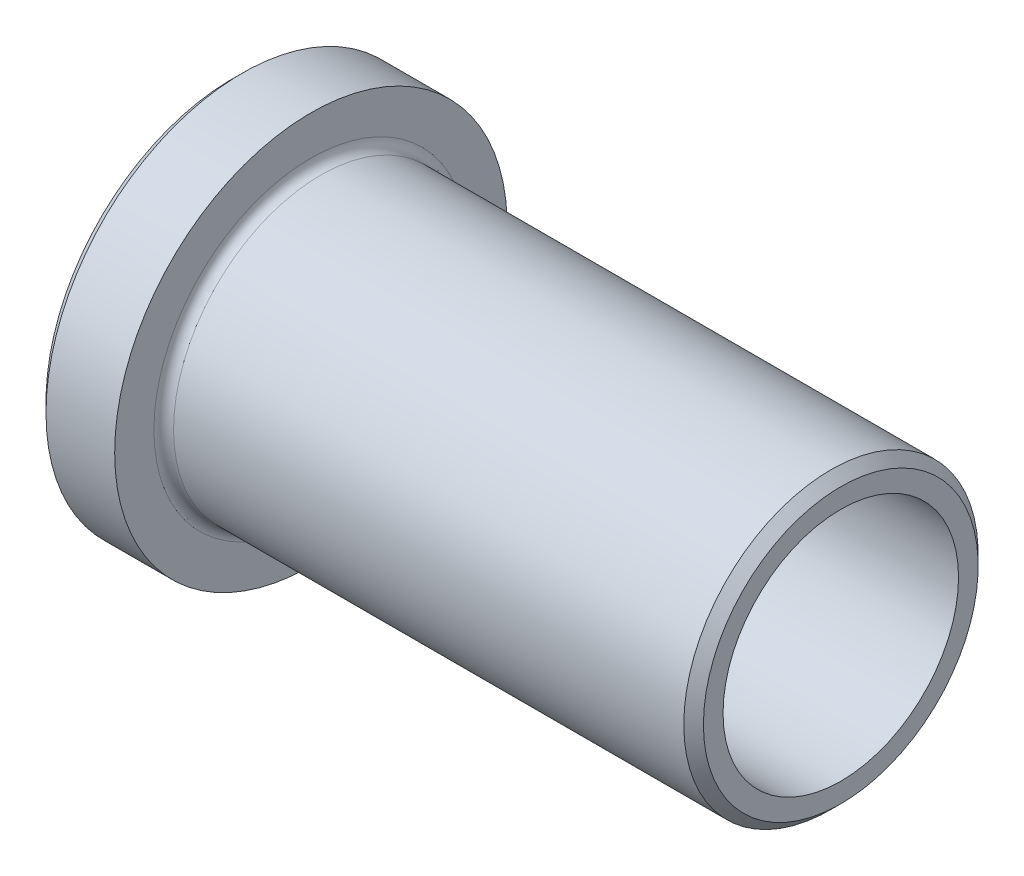
SolidWorks part; units mm, degrees
ref_plane "Piano frontale" through (0, 0, 0) normal (0, 0, 1) x (1, 0, 0)
ref_plane "Piano superiore" through (0, 0, 0) normal (0, 1, 0) x (1, 0, 0)
ref_plane "Piano destro" through (0, 0, 0) normal (1, 0, 0) x (0, 0, -1)
sketch "Sketch1" plane through (0, 0, 0) normal (0, 0, 1) x (1, 0, 0)
  line L0 (-6.1144, 0) -> (31, 0) construction
  line L1 (0, 6) -> (0, 10)
  line L2 (0, 10) -> (4, 10)
  line L3 (4, 10) -> (4, 7.5)
  line L4 (4, 7.5) -> (31, 7.5)
  line L5 (31, 7.5) -> (31, 6)
  line L6 (31, 6) -> (0, 6)
  dimension "D1" = 31
  dimension "D2" = 27
  dimension "D3" = 10
  dimension "D4" = 7.5
  dimension "D5" = 6
revolve "Revolve1" add sketch "Sketch1" angle 360 about L0
fillet "Fillet1" radius 0.5 1 edges at (4, 0, 7.5)
chamfer "Chamfer1" distance 0.5 angle 45 2 edges at (31, 0, 7.5) (0, 0, 10)
